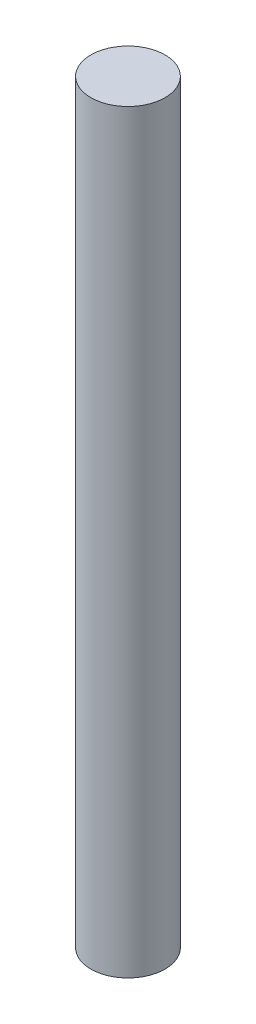
SolidWorks part; units mm, degrees
ref_plane "Front Plane" through (0, 0, 0) normal (0, 0, 1) x (1, 0, 0)
ref_plane "Top Plane" through (0, 0, 0) normal (0, 1, 0) x (1, 0, 0)
ref_plane "Right Plane" through (0, 0, 0) normal (1, 0, 0) x (0, 0, -1)
sketch "Sketch1" plane through (0, 0, 0) normal (0, 1, 0) x (1, 0, 0)
  circle A0 centre (0, 0) radius 28
  circle A1 centre (0, 0) radius 26
  dimension "D1" = 56
  dimension "D2" = 2
extrude "Boss-Extrude1" add sketch "Sketch1" along normal blind 570
sketch "Sketch2" plane through (0, 570, 0) normal (0, 1, 0) x (1, 0, 0)
  circle A0 centre (0, 0) radius 26 construction
  circle A1 centre (0, 0) radius 26
extrude "Boss-Extrude2" add sketch "Sketch2" against normal blind 2
